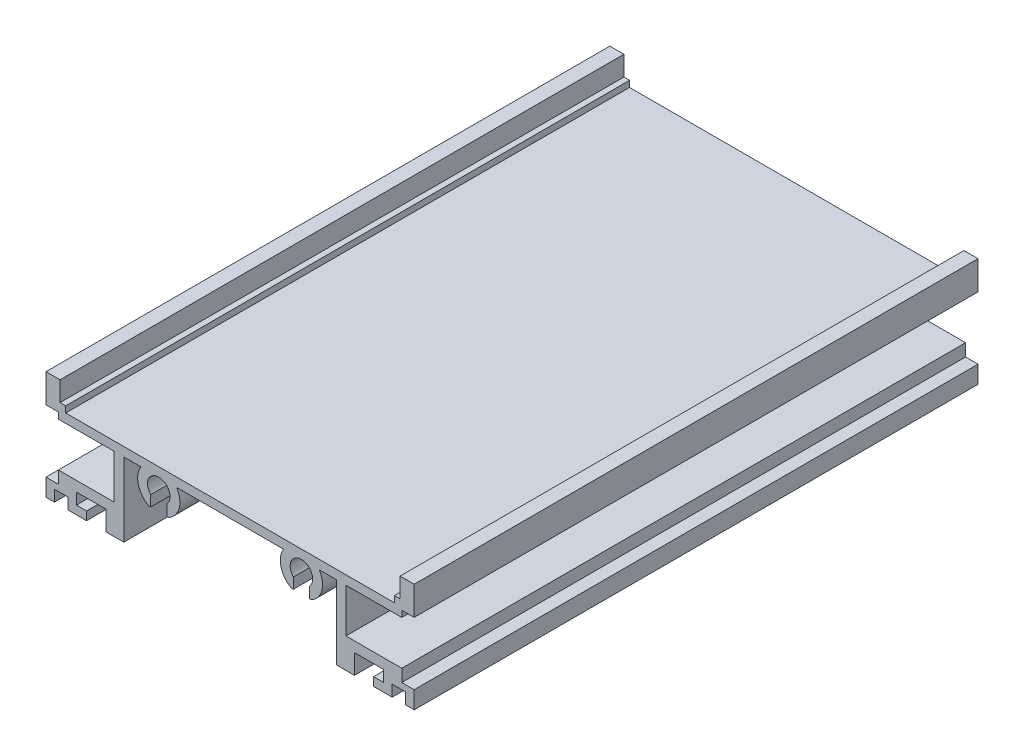
SolidWorks part; units mm, degrees
ref_plane "Piano frontale" through (0, 0, 0) normal (0, 0, 1) x (1, 0, 0)
ref_plane "Piano superiore" through (0, 0, 0) normal (0, 1, 0) x (1, 0, 0)
ref_plane "Piano destro" through (0, 0, 0) normal (1, 0, 0) x (0, 0, -1)
sketch "Schizzo1" plane through (0, 0, 0) normal (0, 0, 1) x (1, 0, 0)
  line L0 (-32.65, 14) -> (-32.65, 8.9)
  line L5 (-32.65, 14) -> (-30.15, 14)
  line L6 (-30.15, 14) -> (-30.15, 10.5)
  line L7 (-32.65, 8.9) -> (-30.45, 8.9)
  line L8 (-30.45, 8.9) -> (-30.45, 7.8)
  line L9 (-30.45, 7.8) -> (-20.55, 7.8)
  line L10 (-20.55, 7.8) -> (-20.55, 0)
  line L11 (-20.55, 0) -> (-30.45, 0)
  line L12 (-30.45, 0) -> (-30.45, -2.2)
  line L13 (-30.45, -2.2) -> (-32.65, -2.2)
  line L14 (-32.65, -2.2) -> (-32.65, -5.3)
  line L15 (-32.65, -5.3) -> (-31.15, -5.3)
  line L16 (-31.15, -5.3) -> (-31.15, -3.3)
  line L17 (-31.15, -3.3) -> (-28.75, -3.3)
  line L18 (-28.75, -3.3) -> (-28.75, -5.3)
  line L19 (-28.75, -5.3) -> (-25.45, -5.3)
  line L20 (-25.45, -5.3) -> (-25.45, -3.8)
  line L21 (-25.45, -3.8) -> (-27.25, -3.8)
  line L22 (-27.25, -3.8) -> (-27.25, -1.8)
  line L23 (-27.25, -1.8) -> (-22.05, -1.8)
  line L24 (-22.05, -1.8) -> (-22.05, -5.3)
  line L25 (-22.05, -5.3) -> (-18.85, -5.3)
  line L26 (-18.85, -5.3) -> (-18.85, 7.8)
  line L27 (-18.85, 7.8) -> (-15.8215, 7.8)
  line L28 (0, 9.4) -> (0, -9.65)
  line L29 (-30.15, 10.5) -> (-29.15, 10.5)
  line L30 (-29.15, 10.5) -> (-29.15, 9.4)
  line L31 (-29.15, 9.4) -> (29.15, 9.4)
  line L32 (11.4, 6.05) -> (-11.4, 6.05) construction
  line L33 (-12.6595, 3.681) -> (-12.5509, 3.8081) construction
  line L35 (-14.0741, 4.4052) -> (-14.0741, 2.5)
  line L37 (-11.2211, 4.4052) -> (-11.2211, 2.5)
  line L38 (-12.7442, 3.8081) -> (-12.6595, 3.681) construction
  line L39 (-14.4234, 2.5) -> (-14.0741, 2.5)
  line L40 (-11.2211, 2.5) -> (-10.8718, 2.5)
  line L41 (-9.4736, 7.8) -> (9.4736, 7.8)
  line L42 (12.7442, 3.8081) -> (12.6595, 3.681) construction
  line L43 (12.6595, 3.681) -> (12.5509, 3.8081) construction
  line L44 (11.2211, 2.5) -> (10.8718, 2.5)
  line L45 (14.4234, 2.5) -> (14.0741, 2.5)
  line L46 (11.2211, 4.4052) -> (11.2211, 2.5)
  line L47 (14.0741, 4.4052) -> (14.0741, 2.5)
  line L48 (29.15, 10.5) -> (29.15, 9.4)
  line L49 (30.15, 10.5) -> (29.15, 10.5)
  line L50 (18.85, 7.8) -> (15.8215, 7.8)
  line L51 (18.85, -5.3) -> (18.85, 7.8)
  line L52 (22.05, -5.3) -> (18.85, -5.3)
  line L53 (22.05, -1.8) -> (22.05, -5.3)
  line L54 (27.25, -1.8) -> (22.05, -1.8)
  line L55 (27.25, -3.8) -> (27.25, -1.8)
  line L56 (25.45, -3.8) -> (27.25, -3.8)
  line L57 (25.45, -5.3) -> (25.45, -3.8)
  line L58 (28.75, -5.3) -> (25.45, -5.3)
  line L59 (28.75, -3.3) -> (28.75, -5.3)
  line L60 (31.15, -3.3) -> (28.75, -3.3)
  line L61 (31.15, -5.3) -> (31.15, -3.3)
  line L62 (32.65, -5.3) -> (31.15, -5.3)
  line L63 (32.65, -2.2) -> (32.65, -5.3)
  line L64 (30.45, -2.2) -> (32.65, -2.2)
  line L65 (30.45, 0) -> (30.45, -2.2)
  line L66 (20.55, 0) -> (30.45, 0)
  line L67 (20.55, 7.8) -> (20.55, 0)
  line L68 (30.45, 7.8) -> (20.55, 7.8)
  line L69 (30.45, 8.9) -> (30.45, 7.8)
  line L70 (32.65, 8.9) -> (30.45, 8.9)
  line L71 (30.15, 14) -> (30.15, 10.5)
  line L72 (32.65, 14) -> (30.15, 14)
  line L73 (32.65, 14) -> (32.65, 8.9)
  arc A0 (-12.7442, 3.8081) -> (-12.5509, 3.8081) centre (-12.6476, 5.8029) ccw
  arc A1 (-15.8215, 7.8) -> (-14.4234, 2.5) centre (-12.6476, 5.8029) ccw
  arc A2 (-10.8718, 2.5) -> (-9.4736, 7.8) centre (-12.6476, 5.8029) ccw
  arc A3 (-11.2211, 4.4052) -> (-14.0741, 4.4052) centre (-12.6476, 5.8029) ccw
  arc A4 (11.2211, 4.4052) -> (14.0741, 4.4052) centre (12.6476, 5.8029) cw
  arc A5 (10.8718, 2.5) -> (9.4736, 7.8) centre (12.6476, 5.8029) cw
  arc A6 (15.8215, 7.8) -> (14.4234, 2.5) centre (12.6476, 5.8029) cw
  arc A7 (12.7442, 3.8081) -> (12.5509, 3.8081) centre (12.6476, 5.8029) cw
  point P0 (0, 0)
  point P6 (-20.45, -5.3)
  point P36 (-12.6595, 3.681)
  point P51 (0, 6.05)
  point P58 (0, 7.8)
  point P86 (12.6595, 3.681)
  dimension "D26" = 7.5
  dimension "D1" = 3.2
  dimension "D2" = 19.3
  dimension "D3" = 13.1
  dimension "D4" = 32.65
  dimension "D5" = 3.4
  dimension "D6" = 3.3
  dimension "D7" = 2.4
  dimension "D8" = 1.5
  dimension "D9" = 2
  dimension "D10" = 5.2
  dimension "D11" = 1.5
  dimension "D12" = 3.5
  dimension "D13" = 19.3
  dimension "D14" = 1.8
  dimension "D15" = 3.1
  dimension "D16" = 2.2
  dimension "D17" = 1.7
  dimension "D18" = 5.1
  dimension "D19" = 13.1
  dimension "D20" = 1.6
  dimension "D21" = 2.5
  dimension "D22" = 3.5
  dimension "D23" = 3.5
  dimension "D24" = 12.65
  dimension "D25" = 1.75
  dimension "D27" = 5.3
extrude "Estrusione-Estrusione1" add sketch "Schizzo1" along normal blind 100 contours A3 L37 L40 A2 L41 L28 L31 L30 L29 L6 L5 L0 L7 L8 L9 L10 L11 L12 L13 L14 L15 L16 L17 L18 L19 L20 L21 L22 L23 L24 L25 L26 L27 A1 L39 L35 | A6 L50 L51 L52 L53 L54 L55 L56 L57 L58 L59 L60 L61 L62 L63 L64 L65 L66 L67 L68 L69 L70 L73 L72 L71 L49 L48 L31 L28 L41 A5 L44 L46 A4 L47 L45
